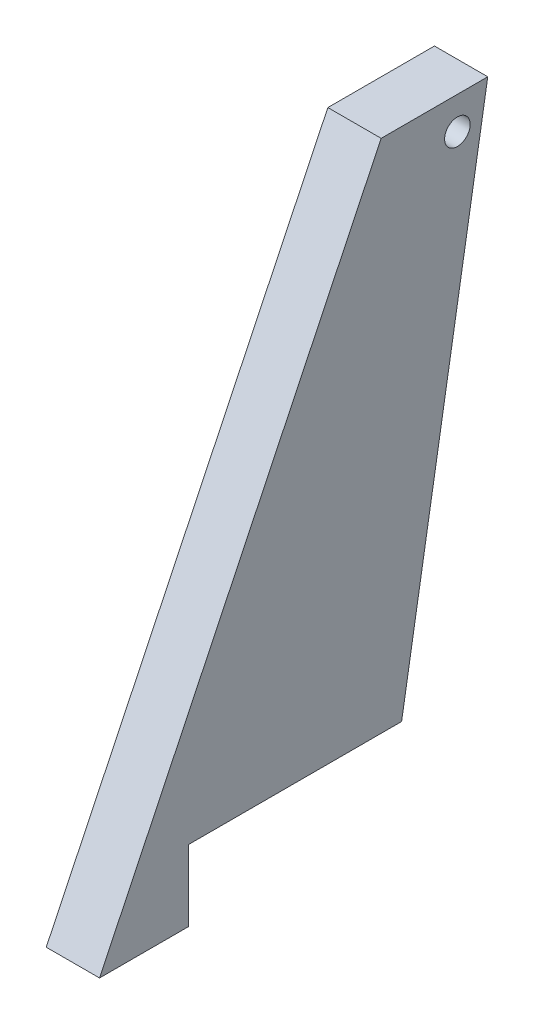
SolidWorks part; units mm, degrees
ref_plane "Front Plane" through (0, 0, 0) normal (0, 0, 1) x (1, 0, 0)
ref_plane "Top Plane" through (0, 0, 0) normal (0, 1, 0) x (1, 0, 0)
ref_plane "Right Plane" through (0, 0, 0) normal (1, 0, 0) x (0, 0, -1)
sketch "Sketch1" plane through (0, 0, 0) normal (1, 0, 0) x (0, 0, -1)
  line L0 (0, 0) -> (-15.875, 0)
  line L4 (0, 12.7) -> (0, 0)
  line L9 (-15.875, 0) -> (34.4445, 104.775)
  line L11 (0, 12.7) -> (38.1, 12.7)
  line L12 (38.1, 12.7) -> (53.4945, 104.775)
  line L13 (53.4945, 104.775) -> (34.4445, 104.775)
  dimension "D1" = 15.875
  dimension "D2" = 19.05
  dimension "D3" = 64.347
  dimension "D4" = 92.075
  dimension "D5" = 12.7
  dimension "D6" = 38.1
extrude "Boss-Extrude1" add sketch "Sketch1" along normal blind 9.525
sketch "Sketch3" plane through (0, 0, 0) normal (-1, 0, 0) x (0, 0, 1)
  line L0 (-26.3006, 92.5359) -> (-56.6382, 77.9658)
  line L1 (-56.6382, 77.9658) -> (-81.9296, 130.6274)
  line L2 (-81.9296, 130.6274) -> (-51.592, 145.1974)
  line L3 (-51.592, 145.1974) -> (-26.3006, 92.5359)
  line L12 (-34.4445, 104.775) -> (15.875, 0) construction
  line L13 (-48.0672, 98.9886) -> (-63.236, 91.7036) construction
  line L14 (-48.0672, 98.9886) -> (-32.8983, 106.2737) construction
  circle A0 centre (-48.0672, 98.9886) radius 15.875 construction
  dimension "D3" = 31.75
  dimension "D1" = 33.655
  dimension "D2" = 58.42
  dimension "D4" = 15.24
sketch "Sketch2" plane through (0, 0, 0) normal (-1, 0, 0) x (0, 0, 1)
  circle A0 centre (-48.0672, 98.9886) radius 2.286
  dimension "D3" = 4.572
  dimension "D1" = 98.9886
  dimension "D2" = 48.0672
extrude "Cut-Extrude1" cut sketch "Sketch2" against normal through all
sketch "Sketch4" plane through (9.525, 0, 0) normal (1, 0, 0) x (0, 0, -1)
  line L0 (0, 0) -> (0, 12.7)
  line L1 (0, 12.7) -> (38.1, 12.7)
  line L2 (38.1, 12.7) -> (81.9296, 130.6274)
  line L3 (81.9296, 130.6274) -> (51.592, 145.1974)
  line L4 (51.592, 145.1974) -> (-18.1409, 0)
  line L5 (-18.1409, 0) -> (0, 0)
